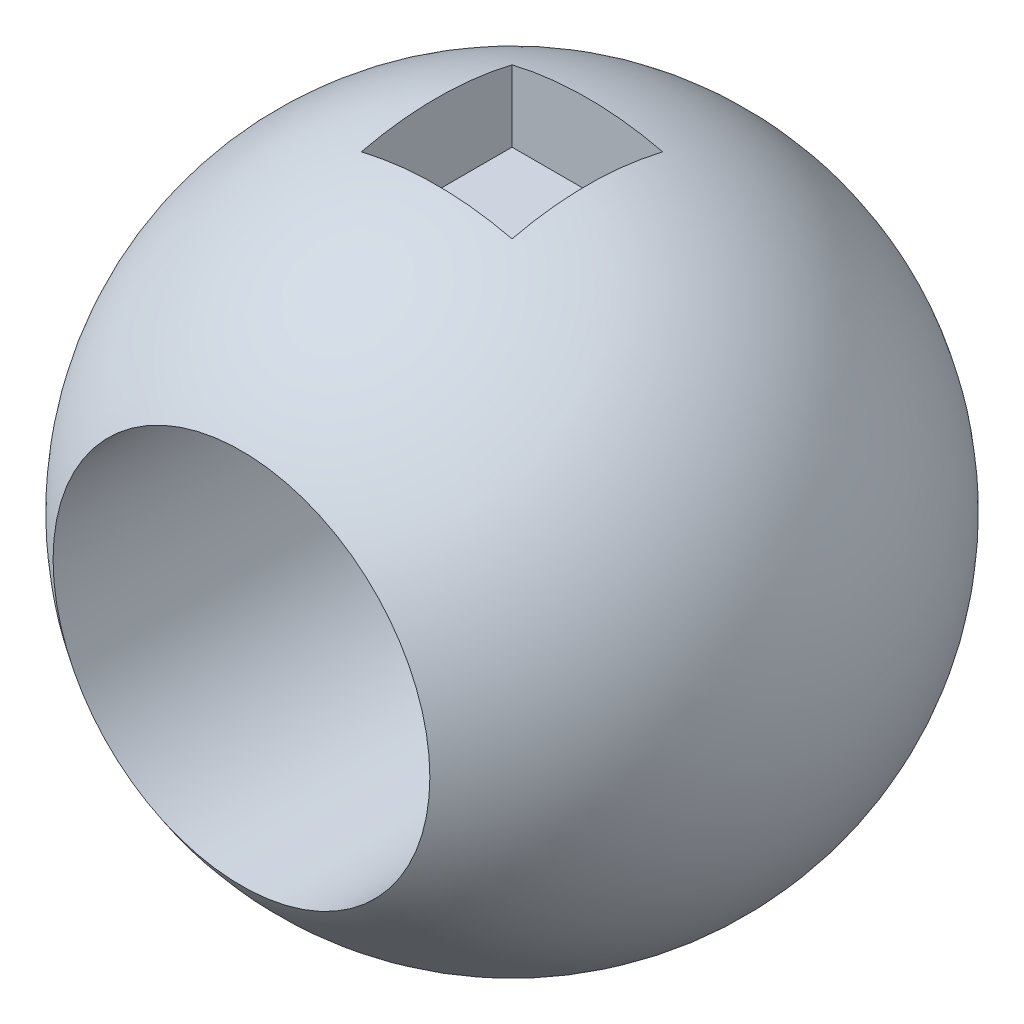
SolidWorks part; units mm, degrees
ref_plane "Front Plane" through (0, 0, 0) normal (0, 0, 1) x (1, 0, 0)
ref_plane "Top Plane" through (0, 0, 0) normal (0, 1, 0) x (1, 0, 0)
ref_plane "Right Plane" through (0, 0, 0) normal (1, 0, 0) x (0, 0, -1)
sketch "Sketch4" plane through (0, 0, 0) normal (0, 1, 0) x (1, 0, 0)
  line L0 (0, 17.4871) -> (0, -17.4871) construction
  line L1 (-12, 18.707) -> (0, 18.707)
  line L2 (0, 18.707) -> (0, -18.707)
  line L3 (0, -18.707) -> (-12, -18.707)
  arc A0 (-12, -18.707) -> (-12, 18.707) centre (0, 0) cw
  point P6 (0, 0)
  dimension "D1" = 22.225
  dimension "D2" = 12
revolve "Revolve4" add sketch "Sketch4" angle 360 about L0
sketch "Sketch5" plane through (0, 0, 18.707) normal (0, 0, 1) x (1, 0, 0)
  circle A0 centre (0, 0) radius 12.7
  dimension "D1" = 25.4
extrude "Cut-Extrude2" cut sketch "Sketch5" against normal through all
ref_plane "Plane1" through (0, 22.225, 0) normal (0, 1, 0) x (1, 0, 0)
sketch "Sketch6" plane through (0, 22.225, 0) normal (0, 1, 0) x (1, 0, 0)
  line L1 (5.08, -5.08) -> (-5.08, -5.08)
  line L2 (5.08, -5.08) -> (5.08, 5.08)
  line L3 (5.08, 5.08) -> (-5.08, 5.08)
  line L4 (-5.08, -5.08) -> (-5.08, 5.08)
  line L5 (5.08, -5.08) -> (-5.08, 5.08) construction
  line L6 (5.08, 5.08) -> (-5.08, -5.08) construction
  point P0 (0, 0)
  dimension "D1" = 10.16
  dimension "D2" = 10.16
extrude "Cut-Extrude3" cut sketch "Sketch6" against normal blind 6
mirror "Mirror1" about plane through (0, 0, 0) normal (0, 1, 0) of "Cut-Extrude3"
